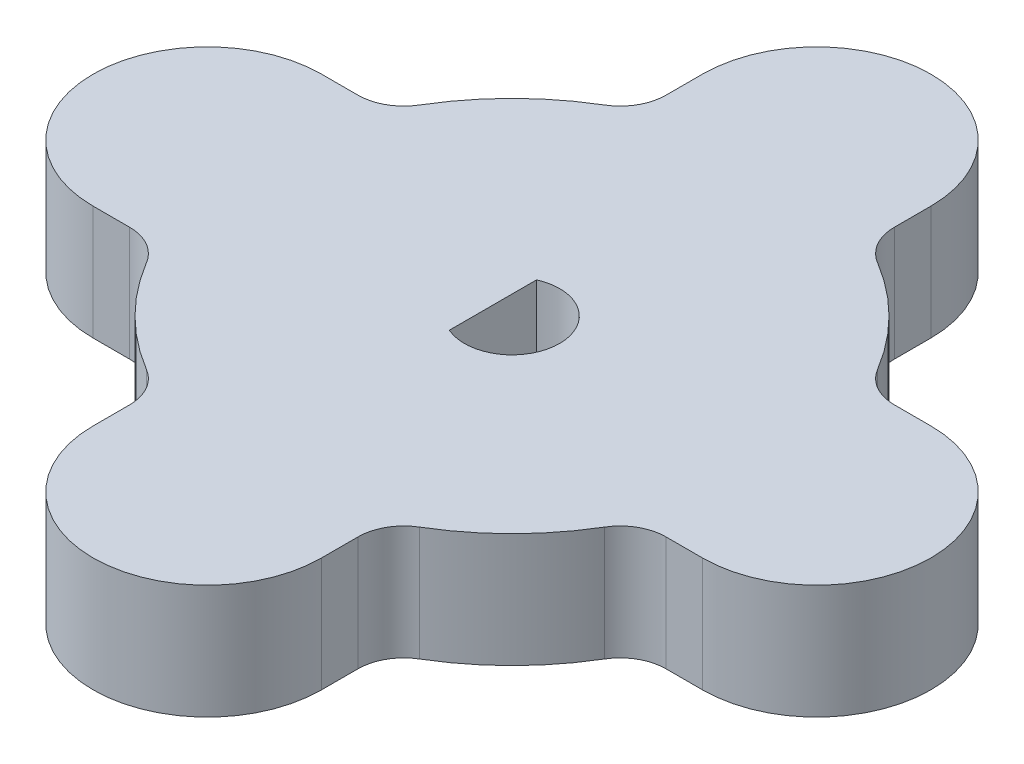
SolidWorks part; units mm, degrees
ref_plane "Front Plane" through (0, 0, 0) normal (0, 0, 1) x (1, 0, 0)
ref_plane "Top Plane" through (0, 0, 0) normal (0, 1, 0) x (1, 0, 0)
ref_plane "Right Plane" through (0, 0, 0) normal (1, 0, 0) x (0, 0, -1)
sketch "Sketch1" plane through (0, 0, 0) normal (0, 1, 0) x (1, 0, 0)
  line L0 (-3.4328, 26.0085) -> (-22.4828, -24.7915) construction
  line L1 (-22.4828, 26.0085) -> (-3.4328, 26.0085)
  line L2 (-22.4828, 26.0085) -> (-22.4828, -24.7915)
  line L3 (-22.4828, -24.7915) -> (-3.4328, -24.7915)
  line L4 (-3.4328, 26.0085) -> (-3.4328, -24.7915)
  line L5 (-38.3578, 10.1335) -> (12.4422, 10.1335)
  line L6 (-38.3578, 10.1335) -> (-38.3578, -8.9165)
  line L7 (-38.3578, -8.9165) -> (12.4422, -8.9165)
  line L8 (12.4422, 10.1335) -> (12.4422, -8.9165)
  line L9 (-38.3578, 10.1335) -> (12.4422, -8.9165) construction
  circle A0 centre (-12.9578, 0.6085) radius 22.225
  arc A1 (-38.3578, 10.1335) -> (-38.3578, -8.9165) centre (-38.3578, 0.6085) ccw
  arc A2 (-22.4828, 26.0085) -> (-3.4328, 26.0085) centre (-12.9578, 26.0085) cw
  arc A3 (12.4422, 10.1335) -> (12.4422, -8.9165) centre (12.4422, 0.6085) cw
  arc A4 (-3.4328, -24.7915) -> (-22.4828, -24.7915) centre (-12.9578, -24.7915) cw
  point P14 (-12.9578, 0.6085)
  point P15 (-12.9578, 0.6085)
  dimension "D1" = 44.45
  dimension "D2" = 19.05
  dimension "D3" = 19.05
  dimension "D4" = 50.8
  dimension "D5" = 50.8
extrude "Boss-Extrude1" add sketch "Sketch1" along normal blind 9.525 contours A0 L4 L1 L2 | L4 A0 L2 L5 | A2 L1 | L2 L7 L4 L5 | L5 A0 L7 L2 | A0 L5 L6 L7 | L6 A1 | L7 A0 L2 | L2 A0 L4 L7 | A0 L2 L3 L4 | A4 L3 | L5 A0 L4 | L7 A0 L5 L4 | L4 A0 L7 | A0 L7 L8 L5 | A3 L8 | L2 A0 L5
fillet "Fillet1" radius 3.81 8 edges at (7.1226, 4.7625, -10.1335) (-33.0383, 4.7625, -10.1335) (-22.4828, 4.7625, -20.6889) (-22.4828, 4.7625, 19.472) (7.1226, 4.7625, 8.9165) (-33.0383, 4.7625, 8.9165) (-3.4328, 4.7625, -20.6889) (-3.4328, 4.7625, 19.472)
sketch "Sketch2" plane through (0, 9.525, 0) normal (0, 1, 0) x (1, 0, 0)
  line L0 (-14.5453, 4.2459) -> (-14.5453, -3.0289)
  line L1 (-14.5453, 0.6085) -> (-8.9891, 0.6085)
  circle A0 centre (-12.9578, 0.6085) radius 3.9688
  arc A1 (-24.3414, 19.6969) -> (-32.0462, 11.992) centre (-12.9578, 0.6085) ccw construction
  dimension "D1" = 7.9375
  dimension "D2" = 5.5562
extrude "Cut-Extrude1" cut sketch "Sketch2" against normal through all contours L1 A0 L0 | L0 A0 L1
